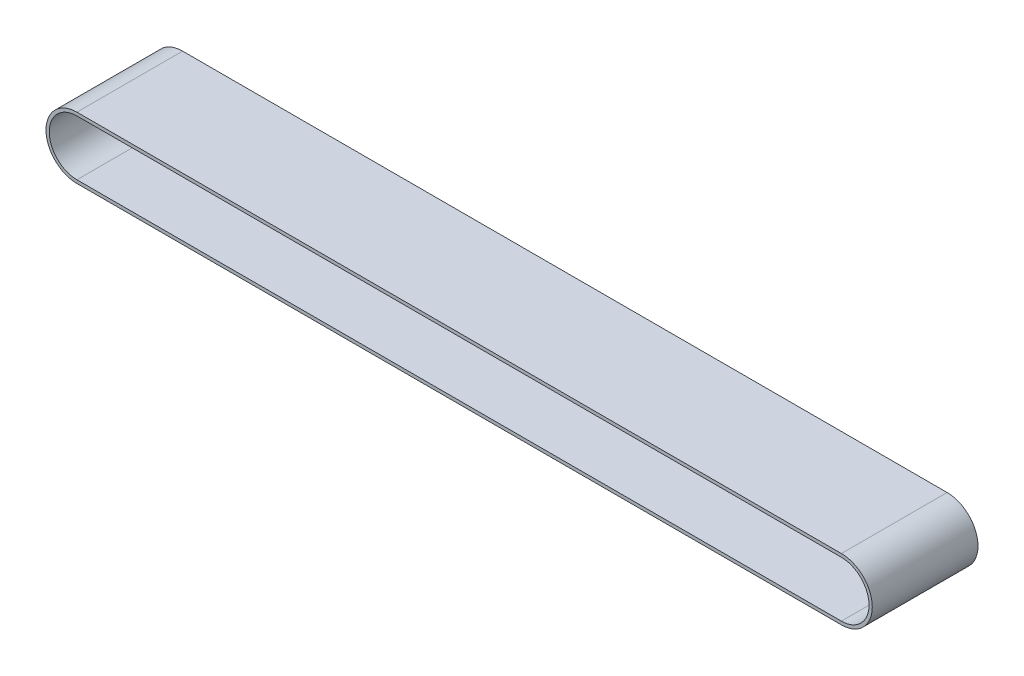
SolidWorks part; units mm, degrees
ref_plane "Front Plane" through (0, 0, 0) normal (0, 0, 1) x (1, 0, 0)
ref_plane "Top Plane" through (0, 0, 0) normal (0, 1, 0) x (1, 0, 0)
ref_plane "Right Plane" through (0, 0, 0) normal (1, 0, 0) x (0, 0, -1)
sketch "Sketch1" plane through (0, 0, 0) normal (0, 0, 1) x (1, 0, 0)
  line L0 (0, 18) -> (470, 18)
  line L1 (0, -18) -> (470, -18)
  arc A0 (0, 18) -> (0, -18) centre (0, 0) ccw
  arc A1 (470, -18) -> (470, 18) centre (470, 0) ccw
  dimension "D1" = 36
  dimension "D2" = 470
extrude "Boss-Extrude1" add sketch "Sketch1" along normal blind 65
sketch "Sketch2" plane through (0, 0, 65) normal (0, 0, 1) x (1, 0, 0)
  line L6 (0, -16) -> (470, -16)
  line L7 (470, 16) -> (0, 16)
  line L8 (0, -16) -> (470, -16)
  line L9 (470, 16) -> (0, 16)
  arc A6 (0, 16) -> (0, -16) centre (0, 0) ccw
  arc A7 (470, -16) -> (470, 16) centre (470, 0) ccw
  arc A8 (0, 16) -> (0, -16) centre (0, 0) ccw
  arc A9 (470, -16) -> (470, 16) centre (470, 0) ccw
  dimension "D1" = 2
extrude "Cut-Extrude1" cut sketch "Sketch2" against normal blind 150 contours L9 A8 L8 A9
sketch "Sketch3" plane through (0, 0, 65) normal (0, 0, 1) x (1, 0, 0)
  line L4 (0, -20) -> (470, -20)
  line L5 (470, 20) -> (0, 20)
  line L6 (0, -20) -> (470, -20)
  line L7 (470, 20) -> (0, 20)
  arc A4 (0, 20) -> (0, -20) centre (0, 0) ccw
  arc A5 (470, -20) -> (470, 20) centre (470, 0) ccw
  arc A6 (0, 20) -> (0, -20) centre (0, 0) ccw
  arc A7 (470, -20) -> (470, 20) centre (470, 0) ccw
  dimension "D1" = 2
extrude "Boss-Extrude2" add sketch "Sketch3" against normal up to surface (65 mm away) up to face at (235, 0, 0)
sketch "Sketch4" plane through (0, 0, 65) normal (0, 0, 1) x (1, 0, 0)
  line L4 (0, -18) -> (470, -18)
  line L5 (470, 18) -> (0, 18)
  line L6 (0, -18) -> (470, -18)
  line L7 (470, 18) -> (0, 18)
  arc A4 (0, 18) -> (0, -18) centre (0, 0) ccw
  arc A5 (470, -18) -> (470, 18) centre (470, 0) ccw
  arc A6 (0, 18) -> (0, -18) centre (0, 0) ccw
  arc A7 (470, -18) -> (470, 18) centre (470, 0) ccw
  dimension "D1" = 2
extrude "Cut-Extrude2" cut sketch "Sketch4" against normal blind 168
sketch "Sketch5" plane through (0, 0, 65) normal (0, 0, 1) x (1, 0, 0)
  line L4 (0, -18) -> (470, -18)
  line L5 (470, 18) -> (0, 18)
  line L6 (0, -18) -> (470, -18)
  line L7 (470, 18) -> (0, 18)
  arc A4 (0, 18) -> (0, -18) centre (0, 0) ccw
  arc A5 (470, -18) -> (470, 18) centre (470, 0) ccw
  arc A6 (0, 18) -> (0, -18) centre (0, 0) ccw
  arc A7 (470, -18) -> (470, 18) centre (470, 0) ccw
  dimension "D1" = 2
extrude "Boss-Extrude4" add sketch "Sketch5" against normal up to surface (65 mm away) contours A6 L6 A7 L7 up to face at (235, 0, 0)
sketch "Sketch7" plane through (0, 0, 65) normal (0, 0, 1) x (1, 0, 0)
  line L4 (0, -17) -> (470, -17)
  line L5 (470, 17) -> (0, 17)
  line L6 (0, -17) -> (470, -17)
  line L7 (470, 17) -> (0, 17)
  arc A4 (0, 17) -> (0, -17) centre (0, 0) ccw
  arc A5 (470, -17) -> (470, 17) centre (470, 0) ccw
  arc A6 (0, 17) -> (0, -17) centre (0, 0) ccw
  arc A7 (470, -17) -> (470, 17) centre (470, 0) ccw
  dimension "D1" = 3
extrude "Cut-Extrude3" cut sketch "Sketch7" against normal blind 225
sketch "Sketch8" plane through (0, 0, 65) normal (0, 0, 1) x (1, 0, 0)
  line L0 (0, 0) -> (470, 0) construction
  line L1 (0, 20) -> (470, 20)
  line L2 (0, -20) -> (470, -20)
  line L3 (0, 0) -> (470, 0) construction
  line L4 (0, 19) -> (470, 19)
  line L5 (0, -19) -> (470, -19)
  arc A0 (0, 20) -> (0, -20) centre (0, 0) ccw
  arc A1 (470, -20) -> (470, 20) centre (470, 0) ccw
  arc A2 (470, -20) -> (470, 20) centre (470, 0) ccw construction
  arc A3 (0, 19) -> (0, -19) centre (0, 0) ccw
  arc A4 (470, -19) -> (470, 19) centre (470, 0) ccw
  point P4 (235, 0)
  point P14 (235, 0)
  dimension "D1" = 19
extrude "Cut-Extrude4" cut sketch "Sketch8" against normal blind 225
